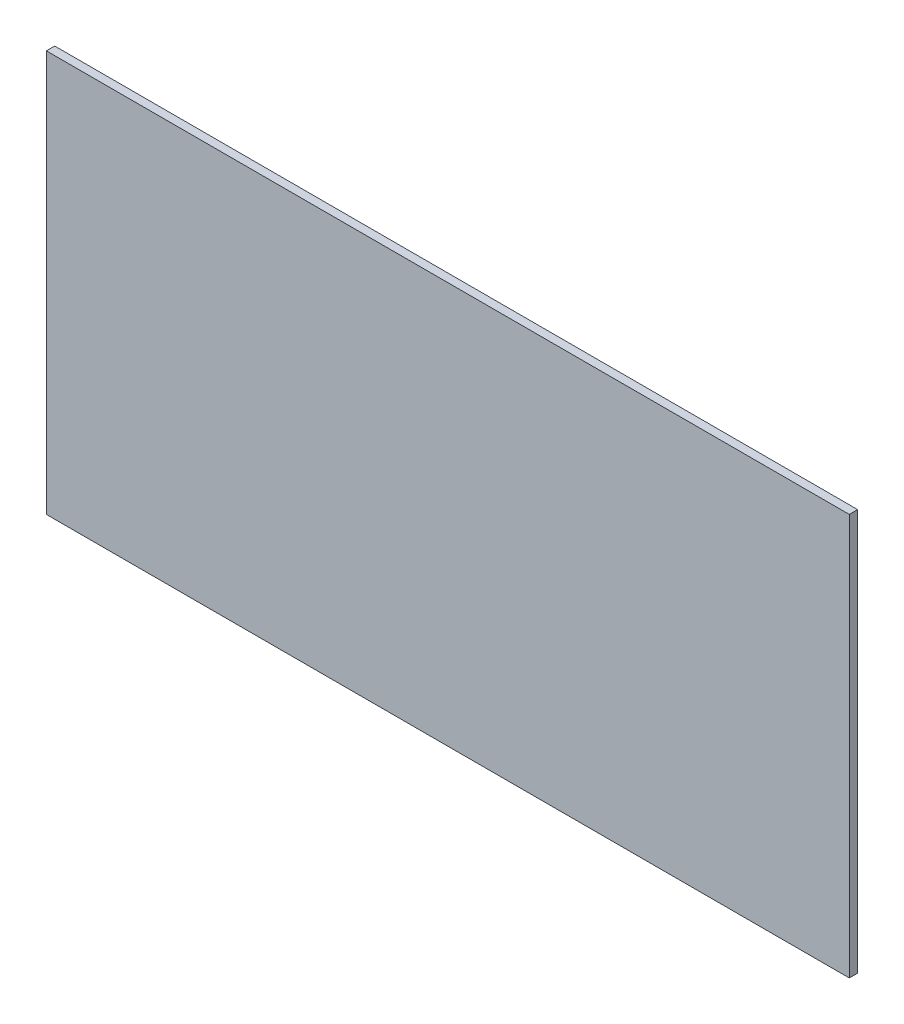
SolidWorks part; units mm, degrees
ref_plane "Front" through (0, 0, 0) normal (0, 0, 1) x (1, 0, 0)
ref_plane "Top" through (0, 0, 0) normal (0, 1, 0) x (1, 0, 0)
ref_plane "Right" through (0, 0, 0) normal (1, 0, 0) x (0, 0, -1)
sketch "Sketch1" plane through (0, 0, 0) normal (0, 0, 1) x (1, 0, 0)
  line L1 (-287.4019, 176.436) -> (322.1981, 176.436)
  line L2 (-287.4019, 176.436) -> (-287.4019, -128.364)
  line L3 (-287.4019, -128.364) -> (322.1981, -128.364)
  line L4 (322.1981, 176.436) -> (322.1981, -128.364)
  dimension "D1" = 304.8
  dimension "D2" = 609.6
extrude "Boss-Extrude1" add sketch "Sketch1" along normal blind 6.35
